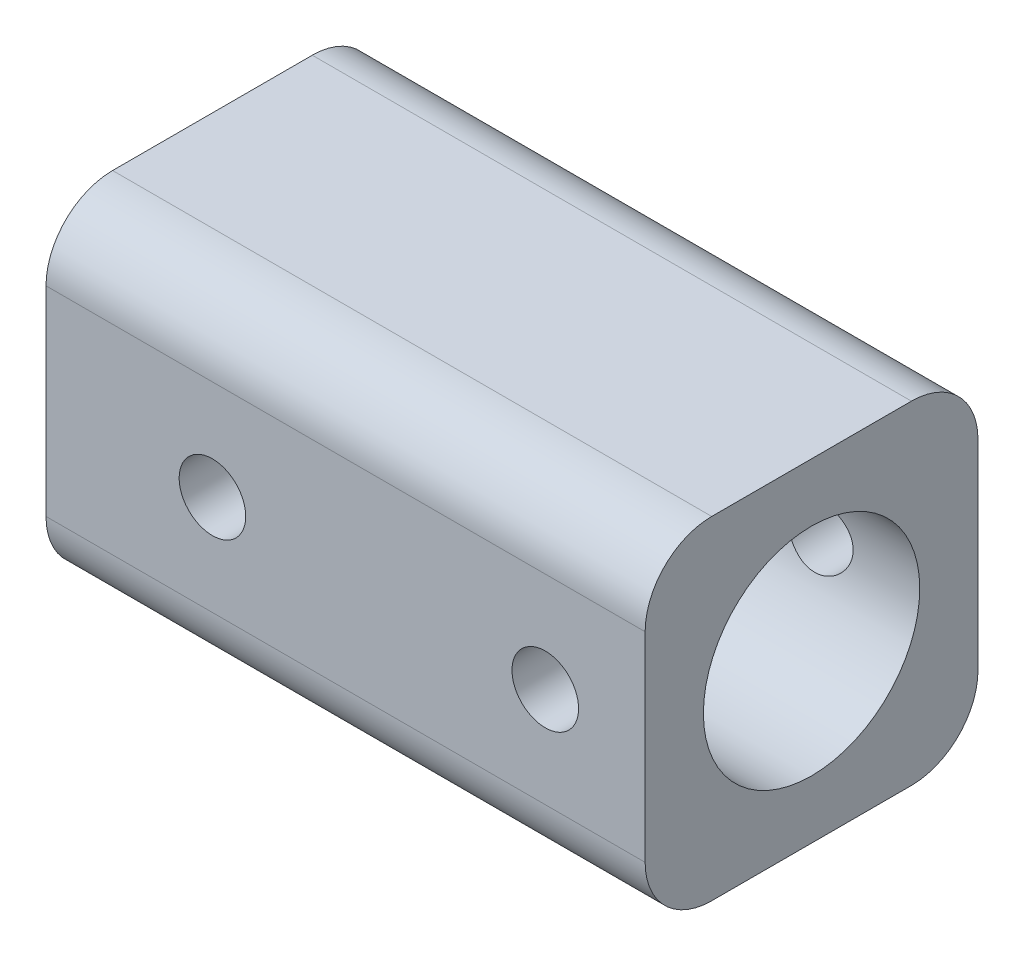
SolidWorks part; units mm, degrees
ref_plane "前视基准面" through (0, 0, 0) normal (0, 0, 1) x (1, 0, 0)
ref_plane "上视基准面" through (0, 0, 0) normal (0, 1, 0) x (1, 0, 0)
ref_plane "右视基准面" through (0, 0, 0) normal (1, 0, 0) x (0, 0, -1)
other "Configuration Table"
sketch "草图1" plane through (0, 0, 0) normal (1, 0, 0) x (0, 0, -1)
  line L1 (0, 0) -> (-10, 0)
  line L2 (0, 0) -> (0, 10)
  line L3 (0, 10) -> (-10, 10)
  line L4 (-10, 0) -> (-10, 10)
  dimension "D1" = 10
  dimension "D2" = 10
extrude "凸台-拉伸2" add sketch "草图1" along normal blind 18 contours L4 L3 L2 L1
sketch "草图2" plane through (18, 0, 0) normal (1, 0, 0) x (0, 0, -1)
  line L0 (-5, 0) -> (-5, 10) construction
  line L1 (0, 0) -> (-10, 0) construction
  line L2 (0, 10) -> (-10, 10) construction
  circle A0 centre (-5, 5) radius 3.25
  dimension "D1" = 6.5
extrude "切除-拉伸1" cut sketch "草图2" against normal blind 9
sketch "草图3" plane through (0, 0, 0) normal (-1, 0, 0) x (0, 0, 1)
  line L0 (5, 0) -> (5, 10) construction
  line L1 (0, 0) -> (10, 0) construction
  line L2 (0, 10) -> (10, 10) construction
  circle A0 centre (5, 5) radius 3
  dimension "D1" = 6
extrude "切除-拉伸2" cut sketch "草图3" against normal blind 15
sketch "草图4" plane through (0, 0, 0) normal (0, 0, -1) x (-1, 0, 0)
  line L0 (0, 5) -> (-18, 5) construction
  line L1 (0, 0) -> (0, 10) construction
  line L2 (-18, 0) -> (-18, 10) construction
  circle A0 centre (-15, 5) radius 1
  circle A1 centre (-5, 5) radius 1
  dimension "D3" = 2
  dimension "D4" = 2
  dimension "D1" = 3
  dimension "D2" = 5
extrude "切除-拉伸3" cut sketch "草图4" against normal blind 10
fillet "圆角1" radius 2 4 edges at (9, 0, 0) (9, 10, 0) (9, 10, 10) (9, 0, 10)
